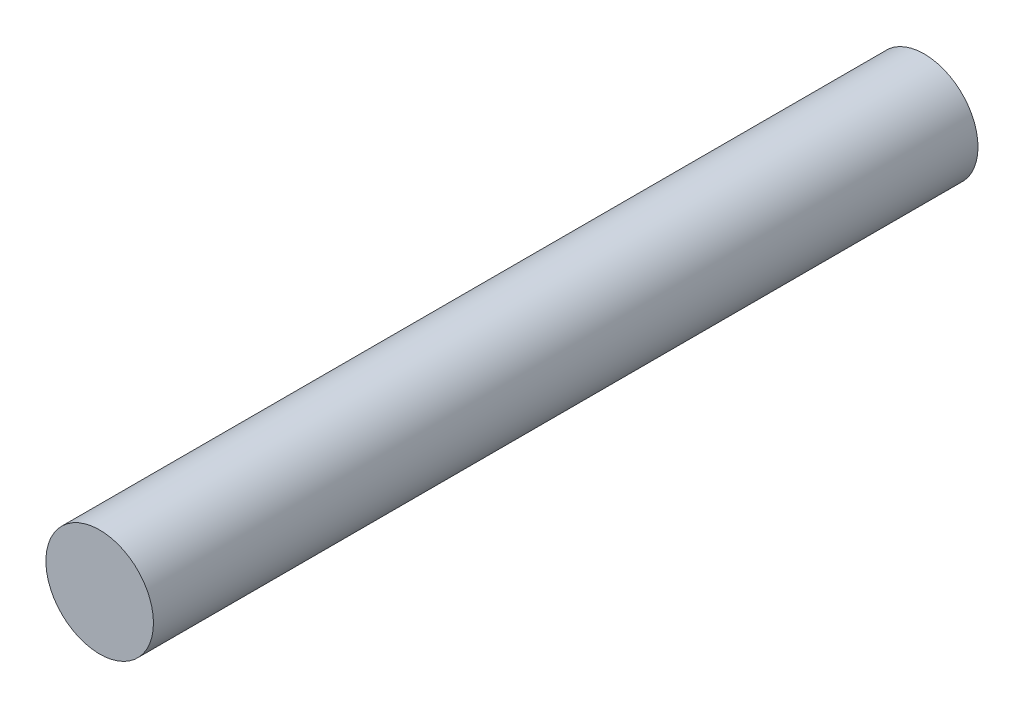
SolidWorks part; units mm, degrees
ref_plane "Front Plane" through (0, 0, 0) normal (0, 0, 1) x (1, 0, 0)
ref_plane "Top Plane" through (0, 0, 0) normal (0, 1, 0) x (1, 0, 0)
ref_plane "Right Plane" through (0, 0, 0) normal (1, 0, 0) x (0, 0, -1)
sketch "Sketch1" plane through (0, 0, 0) normal (0, 0, 1) x (1, 0, 0)
  circle A0 centre (-46, 0) radius 1.5
extrude "Boss-Extrude1" add sketch "Sketch1" against normal up to surface (23 mm away)
